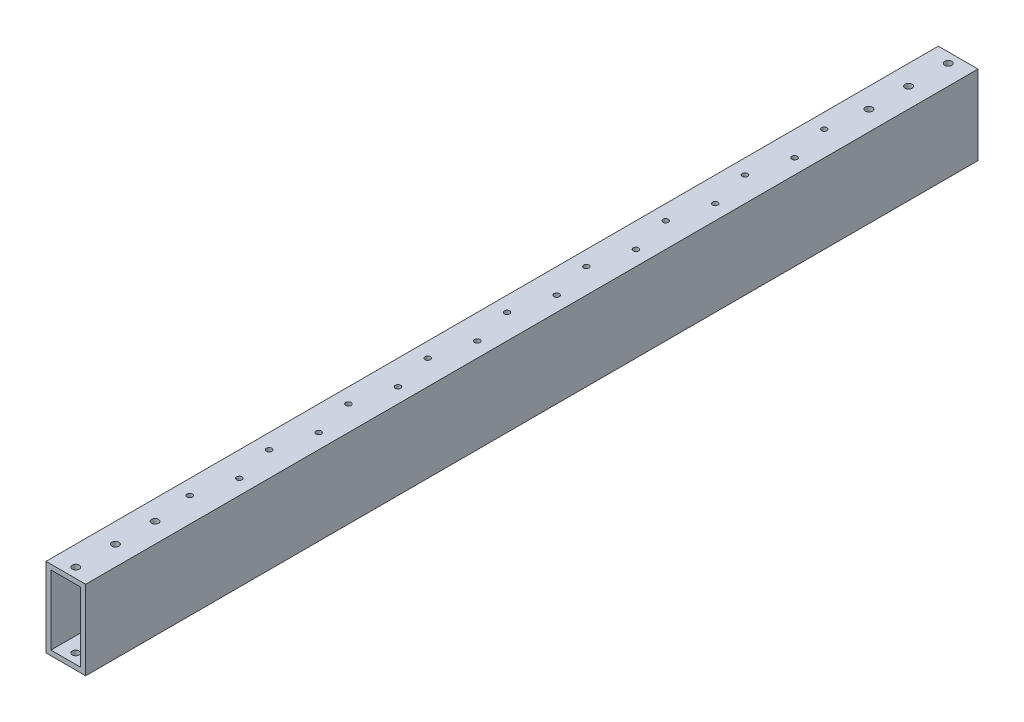
SolidWorks part; units mm, degrees
material "6061-T6 (SS)"
ref_plane "Front Plane" through (0, 0, 0) normal (0, 0, 1) x (1, 0, 0)
ref_plane "Top Plane" through (0, 0, 0) normal (0, 1, 0) x (1, 0, 0)
ref_plane "Right Plane" through (0, 0, 0) normal (1, 0, 0) x (0, 0, -1)
sketch "Sketch1" plane through (0, 0, 0) normal (0, 0, 1) x (1, 0, 0)
  line L1 (-12.7, -25.4) -> (12.7, -25.4)
  line L2 (-12.7, -25.4) -> (-12.7, 25.4)
  line L3 (-12.7, 25.4) -> (12.7, 25.4)
  line L4 (12.7, -25.4) -> (12.7, 25.4)
  line L5 (-12.7, -25.4) -> (12.7, 25.4) construction
  line L6 (-12.7, 25.4) -> (12.7, -25.4) construction
  point P0 (0, 0)
  dimension "D1" = 50.8
  dimension "D2" = 25.4
extrude "Extrude-Thin1" add sketch "Sketch1" along normal blind 571.5 thin thin type one direction reverse wall 3.175
hole_wizard "#8 Clearance Hole1" positions "3DSketch1" profile "Sketch3" hole size "#8" standard "ANSI Inch" end condition through all
sketch3d "3DSketch1"
  line L1 (12.7, 25.4, 0) -> (-12.7, 25.4, 0) construction
  line L6 (0, 25.4, 571.5) -> (0, 25.4, 0) construction
  line L7 (12.7, 25.4, 571.5) -> (-12.7, 25.4, 571.5) construction
  point P57 (0, 25.4, 6.35)
  point P59 (0, 25.4, 31.75)
  point P61 (0, 25.4, 57.15)
  point P63 (0, 25.4, 539.75)
  point P65 (0, 25.4, 514.35)
  point P67 (0, 25.4, 565.15)
  dimension "D1" = 25.4
  dimension "D2" = 25.4
  dimension "D3" = 6.35
  dimension "D4" = 25.4
  dimension "D5" = 25.4
  dimension "D6" = 6.35
sketch "Sketch3" plane through (0, 25.4, 565.15) normal (1, 0, 0) x (0, 0, 1)
  line L0 (0, 0) -> (0, 50.8)
  line L1 (0, 50.8) -> (2.2479, 50.8)
  line L2 (2.2479, 50.8) -> (2.2479, 0)
  line L5 (2.2479, 0) -> (0, 0)
  line L11 (0, -6.35) -> (0, 107.95) construction
  dimension "Thru Hole Dia." = 4.4958
  dimension "Thru Hole Depth" = 50.8
hole_wizard "1/8 (0.135) Diameter Hole1" positions "Sketch4" profile "Sketch5" hole size "1/8" standard "ANSI Inch"
sketch "Sketch4" plane through (0, 25.4, 0) normal (0, 1, 0) x (1, 0, 0)
  point P145 (-3.175, -82.5557)
  point P148 (3.175, -107.9557)
  point P151 (-3.175, -133.3557)
  point P154 (3.175, -158.7557)
  point P157 (-3.175, -184.1557)
  point P160 (3.175, -209.5557)
  point P163 (-3.175, -234.9557)
  point P166 (3.175, -260.3557)
  point P169 (-3.175, -285.7557)
  point P172 (3.175, -311.1557)
  point P175 (-3.175, -336.5557)
  point P178 (3.175, -361.9557)
  point P181 (-3.175, -387.3557)
  point P184 (3.175, -412.7557)
  point P187 (-3.175, -438.1557)
  point P190 (3.175, -463.5557)
  point P193 (-3.175, -488.9557)
sketch "Sketch5" plane through (-3.175, 25.4, 82.5557) normal (1, 0, 0) x (0, 0, 1)
  line L0 (0, 0) -> (0, 3.175)
  line L1 (0, 3.175) -> (1.7145, 3.175)
  line L2 (1.7145, 3.175) -> (1.7145, 0)
  line L5 (1.7145, 0) -> (0, 0)
  line L11 (0, -6.35) -> (0, 107.95) construction
  dimension "Thru Hole Dia." = 3.429
  dimension "Thru Hole Depth" = 3.175
